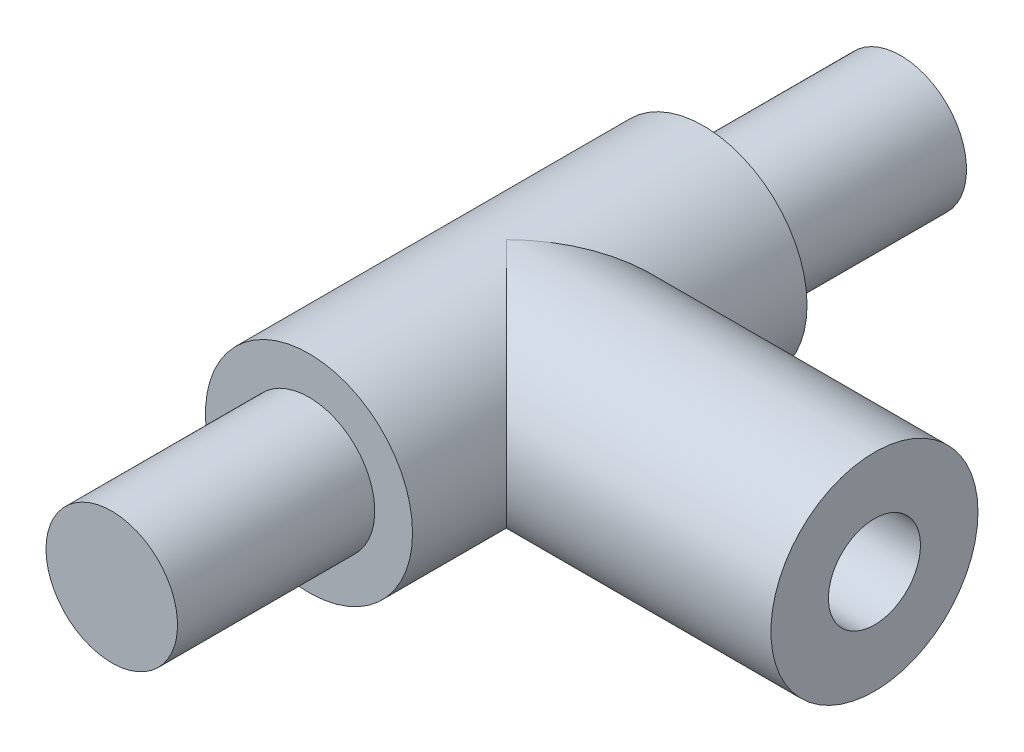
SolidWorks part; units mm, degrees
ref_plane "Front Plane" through (0, 0, 0) normal (0, 0, 1) x (1, 0, 0)
ref_plane "Top Plane" through (0, 0, 0) normal (0, 1, 0) x (1, 0, 0)
ref_plane "Right Plane" through (0, 0, 0) normal (1, 0, 0) x (0, 0, -1)
sketch "Sketch1" plane through (0, 0, 0) normal (0, 0, 1) x (1, 0, 0)
  circle A0 centre (0, 0) radius 5
  dimension "D1" = 10
extrude "Boss-Extrude1" add sketch "Sketch1" along normal mid plane 19.05
sketch "Sketch5" plane through (0, 0, 0) normal (0, 0, 1) x (1, 0, 0)
  circle A0 centre (0, 0) radius 3.175
  dimension "D1" = 6.35
extrude "Boss-Extrude4" add sketch "Sketch5" along normal mid plane 38.1
sketch "Sketch6" plane through (0, 0, 0) normal (1, 0, 0) x (0, 0, -1)
  circle A0 centre (0, 0) radius 5
  dimension "D1" = 10
extrude "Boss-Extrude5" add sketch "Sketch6" along normal blind 17.78
sketch "Sketch7" plane through (17.78, 0, 0) normal (1, 0, 0) x (0, 0, -1)
  circle A0 centre (0, 0) radius 2.2225
  dimension "D1" = 4.445
extrude "Cut-Extrude1" cut sketch "Sketch7" against normal blind 12.7
